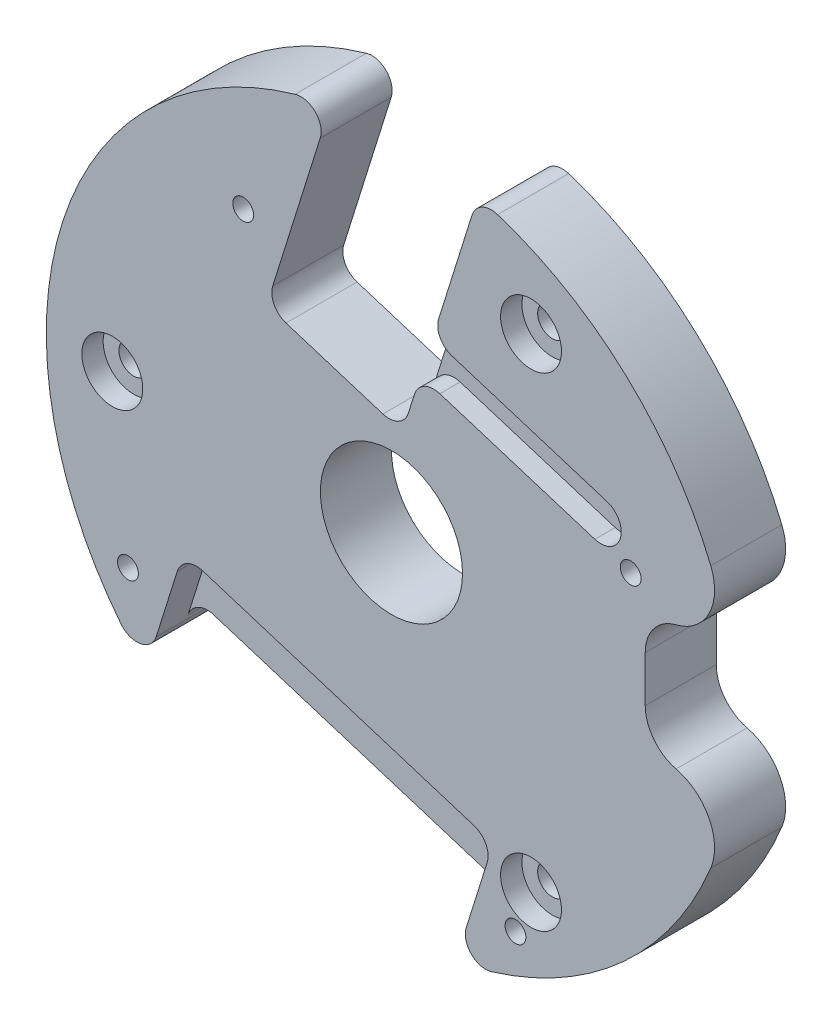
SolidWorks part; units mm, degrees
ref_plane "Front Plane" through (0, 0, 0) normal (0, 0, 1) x (1, 0, 0)
ref_plane "Top Plane" through (0, 0, 0) normal (0, 1, 0) x (1, 0, 0)
ref_plane "Right Plane" through (0, 0, 0) normal (1, 0, 0) x (0, 0, -1)
sketch "Sketch1" plane through (0, 0, 0) normal (0, 0, 1) x (1, 0, 0)
  circle A0 centre (0, 0) radius 34
  circle A1 centre (-27.5, 0) radius 1
  circle A2 centre (13.75, 23.8157) radius 1
  circle A3 centre (13.75, -23.8157) radius 1
  circle A4 centre (0, 0) radius 7
  dimension "D1" = 68
  dimension "D2" = 2
  dimension "D3" = 2
  dimension "D4" = 2
  dimension "D5" = 14
extrude "Boss-Extrude1" add sketch "Sketch1" along normal blind 4 and the other way up to surface (3 mm away) contours A0
sketch "Sketch2" plane through (0, 0, 4) normal (0, 0, 1) x (1, 0, 0)
  line L1 (34, 21.3575) -> (34, -23.6342) construction
  line L2 (33.4664, 6) -> (25, 6)
  line L3 (25, 6) -> (25, -6)
  line L4 (25, -6) -> (33.4664, -6)
  circle A0 centre (0, 0) radius 34 construction
  arc A1 (33.4664, -6) -> (33.4664, 6) centre (0, 0) ccw
  circle A2 centre (0, 0) radius 34 construction
  point P12 (34, 0)
  dimension "D1" = 12
  dimension "D2" = 9
extrude "Cut-Extrude1" cut sketch "Sketch2" against normal up to next
sketch "Sketch4" plane through (0, 0, -4) normal (0, 0, 1) x (1, 0, 0)
  line L0 (-24.2296, -23.8522) -> (-22.4526, -18.1738)
  line L1 (-22.4526, -18.1738) -> (8.0869, -27.7309)
  line L2 (8.0869, -27.7309) -> (6.3099, -33.4094)
  line L3 (-15.2983, -48.8849) -> (0, 0) construction
  line L8 (-20.4855, -21.9328) -> (-10.9419, -24.9194) construction
  line L9 (-5.2157, -26.7114) -> (4.3279, -29.698) construction
  line L14 (-20.4855, -21.9328) -> (-10.9419, -24.9194) construction
  line L15 (-5.2157, -26.7114) -> (4.3279, -29.698) construction
  line L16 (-23.9309, -22.8978) -> (-25.4242, -27.6696) construction
  arc A0 (33.4664, 6) -> (33.4664, -6) centre (0, 0) ccw construction
  arc A1 (-24.2296, -23.8522) -> (6.3099, -33.4094) centre (0, 0) ccw
  circle A2 centre (0, 0) radius 34 construction
  point P8 (-7.1828, -22.9523)
  dimension "D1" = 3
extrude "Cut-Extrude2" cut sketch "Sketch4" along normal up to next
fillet "Fillet1" radius 5 2 edges at (33.4664, -6, 0.5) (33.4664, 6, 0.5)
fillet "Fillet2" radius 4 2 edges at (25, -6, 0.5) (25, 6, 0.5)
sketch "Sketch7" plane through (0, 0, 4) normal (0, 0, 1) x (1, 0, 0)
  point P0 (-25.9564, -15.977)
  point P3 (12.218, -27.9235)
  point P6 (23.5671, 8.3422)
  point P9 (-14.6073, 20.2886)
hole_wizard "M2.5x0.45 Tapped Hole1" positions "Sketch7" profile "Sketch8" tap size "M2.5x0.45" standard "ANSI Metric" end condition up to next
sketch "Sketch8" plane through (-25.9564, -15.977, 4) normal (1, 0, 0) x (0, -1, 0)
  line L0 (0, 0) -> (0, 7)
  line L1 (0, 7) -> (1.025, 7)
  line L2 (1.025, 7) -> (1.025, 0)
  line L5 (1.025, 0) -> (0, 0)
  line L11 (0, -6.35) -> (0, 107.95) construction
  dimension "Thru Tap Drill Dia." = 2.05
  dimension "Thru Tap Drill Depth" = 7
cosmetic thread "Hole Thread1" parameters "D2"=2.5
cosmetic thread "Hole Thread2" parameters "D2"=2.5
cosmetic thread "Hole Thread3" parameters "D2"=2.5
cosmetic thread "Hole Thread4" parameters "D2"=2.5
sketch "Sketch11" plane through (0, 0, 4) normal (0, 0, 1) x (1, 0, 0)
  point P0 (-27.5, 0)
  point P3 (13.75, 23.8157)
  point P10 (13.75, -23.8157)
hole_wizard "CBORE for M2.5 Pan Head Screw1" positions "Sketch11" profile "Sketch12" counterbore size "M2.5" standard "DIN" end condition up to next
sketch "Sketch12" plane through (-27.5, 0, 4) normal (1, 0, 0) x (0, -1, 0)
  line L0 (0, 0) -> (0, 7)
  line L1 (0, 7) -> (1.45, 7)
  line L3 (1.45, 7) -> (1.45, 2.1)
  line L4 (1.45, 2.1) -> (3, 2.1)
  line L5 (3, 2.1) -> (3, 0)
  line L7 (3, 0) -> (0, 0)
  line L11 (0, -6.35) -> (0, 107.95) construction
  dimension "Thru Hole Dia." = 2.9
  dimension "Thru Hole Depth" = 7
  dimension "C'Bore Dia." = 6
  dimension "C'Bore Depth" = 2.1
sketch "Sketch13" plane through (0, 0, -3) normal (0, 0, -1) x (-1, 0, 0)
  circle A3 centre (-13.75, -23.8157) radius 2 construction
  circle A4 centre (-13.75, 23.8157) radius 2 construction
  circle A5 centre (27.5, 0) radius 2 construction
  circle A6 centre (-13.75, -23.8157) radius 2 construction
  circle A7 centre (-13.75, 23.8157) radius 2 construction
  circle A8 centre (27.5, 0) radius 2 construction
  circle A9 centre (-13.75, 23.8157) radius 2.2
  circle A10 centre (27.5, 0) radius 2.2
  circle A11 centre (-13.75, -23.8157) radius 2.2
  dimension "D1" = 0.2
extrude "Cut-Extrude3" cut sketch "Sketch13" against normal blind 3
sketch "Sketch14" plane through (0, 0, 4) normal (0, 0, 1) x (1, 0, 0)
  line L0 (-5.9764, 33.4706) -> (-12.2955, 13.2782)
  line L1 (-12.2955, 13.2782) -> (1.0655, 9.097)
  line L2 (1.0655, 9.097) -> (8.5194, 32.9153)
  line L3 (-4.4203, 15.005) -> (2.3296, 36.5742) construction
  line L7 (-10.1465, 16.797) -> (1.3058, 13.2131)
  line L8 (1.3058, 13.2131) -> (2.7991, 17.9849)
  line L9 (2.7991, 17.9849) -> (-8.6532, 21.5688)
  line L10 (-8.6532, 21.5688) -> (-10.1465, 16.797)
  line L11 (-10.1465, 16.797) -> (1.3058, 13.2131) construction
  line L12 (1.3058, 13.2131) -> (2.7991, 17.9849) construction
  line L13 (2.7991, 17.9849) -> (-8.6532, 21.5688) construction
  line L14 (-8.6532, 21.5688) -> (-10.1465, 16.797) construction
  arc A0 (31.4592, 12.8966) -> (-24.2296, -23.8522) centre (0, 0) ccw construction
  arc A1 (8.5194, 32.9153) -> (-5.9764, 33.4706) centre (0, 0) ccw
  point P11 (-4.4203, 15.005)
  point P14 (-5.615, 11.1876)
  dimension "D2" = 9
  dimension "D3" = 14
  dimension "D1" = 0
extrude "Cut-Extrude4" cut sketch "Sketch14" against normal up to next
fillet "Fillet3" radius 2 8 edges at (8.0869, -27.7309, 0.5) (-22.4526, -18.1738, 0.5) (6.3099, -33.4094, 0.5) (-24.2296, -23.8522, 0.5) (-5.9764, 33.4706, 0.5) (-12.2955, 13.2782, 0.5) (1.0655, 9.097, 0.5) (8.5194, 32.9153, 0.5)
sketch "Sketch15" plane through (0, 0, 4) normal (0, 0, 1) x (1, 0, 0)
  line L0 (6.4484, -32.9668) -> (10.0282, -21.5276)
  line L1 (6.4484, -32.9668) -> (-24.0911, -23.4096)
  line L2 (10.0282, -21.5276) -> (-20.5113, -11.9704)
  line L3 (6.1782, -27.1336) -> (-20.5438, -18.7711) construction
  line L4 (-12.4594, -39.8133) -> (-6.7537, -21.5811) construction
  line L6 (-24.0911, -23.4096) -> (-20.5113, -11.9704)
  line L7 (6.4484, -32.9668) -> (-20.5113, -11.9704) construction
  line L8 (10.0282, -21.5276) -> (-24.0911, -23.4096) construction
  point P1 (-7.0314, -22.4686)
  point P8 (-7.1828, -22.9523)
  point P13 (-5.2415, -16.749)
  dimension "D1" = 6.5
  dimension "D2" = 32
extrude "Cut-Extrude5" cut sketch "Sketch15" against normal blind 3
fillet "Fillet4" radius 2 2 edges at (10.0282, -21.5276, 2.5) (-20.5113, -11.9704, 2.5)
sketch "Sketch16" plane through (0, 0, 4) normal (0, 0, 1) x (1, 0, 0)
  line L0 (-14.5839, 20.2813) -> (23.5671, 8.3422) construction
  line L1 (20.036, 9.4472) -> (2.8575, 14.8231)
  line L2 (20.036, 9.4472) -> (21.2306, 13.2646) construction
  line L3 (2.8575, 14.8231) -> (4.0522, 18.6405)
  line L4 (21.2306, 13.2646) -> (4.0522, 18.6405)
  line L5 (1.6629, 11.0057) -> (7.9343, 31.0459) construction
  circle A0 centre (23.5671, 8.3422) radius 1.025 construction
  circle A1 centre (-14.6073, 20.2886) radius 1.025 construction
  arc A3 (20.036, 9.4472) -> (21.2306, 13.2646) centre (20.6333, 11.3559) ccw
  point P1 (23.5671, 8.3422)
  point P7 (-14.6073, 20.2886)
  dimension "D1" = 4
  dimension "D2" = 18
extrude "Cut-Extrude7" cut sketch "Sketch16" against normal blind 2
fillet "Fillet5" radius 2 2 edges at (2.8575, 14.8231, 3) (4.0522, 18.6405, 3)
